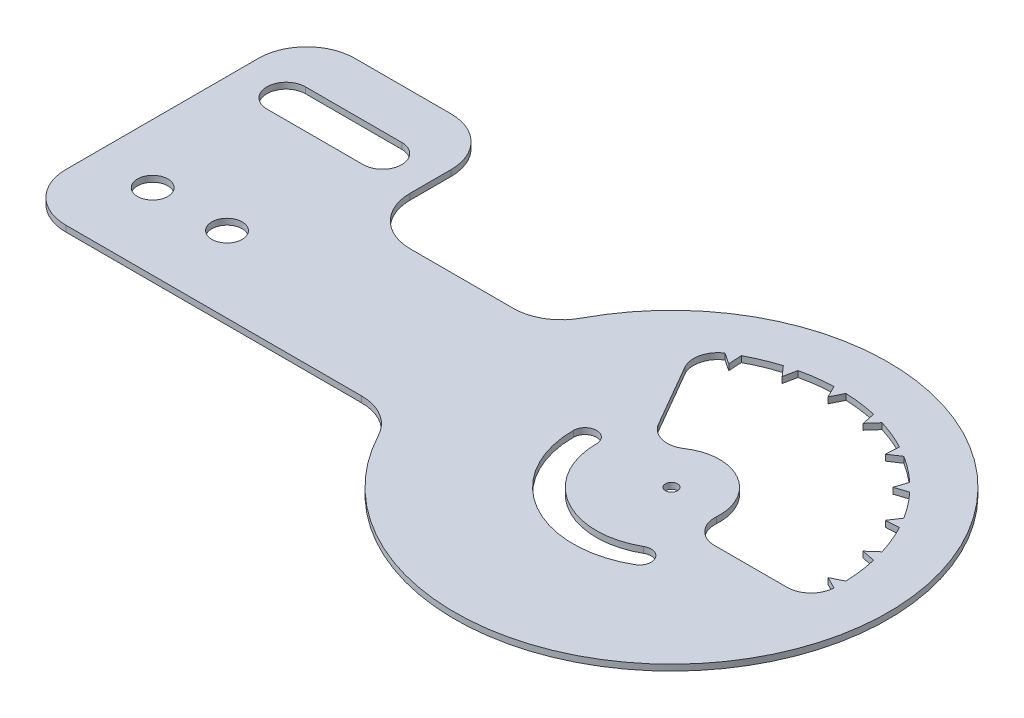
SolidWorks part; units mm, degrees
ref_plane "Front Plane" through (0, 0, 0) normal (0, 0, 1) x (1, 0, 0)
ref_plane "Top Plane" through (0, 0, 0) normal (0, 1, 0) x (1, 0, 0)
ref_plane "Right Plane" through (0, 0, 0) normal (1, 0, 0) x (0, 0, -1)
sketch "Sketch1" plane through (0, 0, 0) normal (0, 1, 0) x (1, 0, 0)
  line L0 (-61.723, 20) -> (-61.723, -20) construction
  line L1 (0, 0) -> (-61.723, 0) construction
  line L2 (-152.4, 43.5) -> (-152.4, -7.3)
  line L3 (-139.7, -20) -> (-61.723, -20)
  line L4 (-139.7, 38.1) -> (-114.3, 38.1) construction
  line L5 (-114.3, 38.1) -> (-101.6, 38.1) construction
  line L6 (-139.7, 38.1) -> (-152.4, 38.1) construction
  line L7 (-139.7, 56.2) -> (-114.3, 56.2)
  line L8 (-101.6, 32.7) -> (-101.6, 43.5)
  line L9 (-139.7, 33.02) -> (-114.3, 33.02)
  line L10 (-139.7, 43.18) -> (-114.3, 43.18)
  line L11 (-152.4, 5.63) -> (-152.4, 16.83) construction
  line L12 (-88.9, 20) -> (-61.723, 20)
  arc A0 (-50.5007, -26.7545) -> (-50.5007, 26.7545) centre (0, 0) ccw
  arc A1 (-61.723, -20) -> (-50.5007, -26.7545) centre (-61.723, -32.7) cw
  arc A2 (-61.723, 20) -> (-50.5007, 26.7545) centre (-61.723, 32.7) ccw
  arc A3 (-88.9, 20) -> (-101.6, 32.7) centre (-88.9, 32.7) cw
  arc A4 (-114.3, 56.2) -> (-101.6, 43.5) centre (-114.3, 43.5) cw
  arc A5 (-152.4, -7.3) -> (-139.7, -20) centre (-139.7, -7.3) ccw
  arc A6 (-152.4, 43.5) -> (-139.7, 56.2) centre (-139.7, 43.5) cw
  arc A7 (-139.7, 33.02) -> (-139.7, 43.18) centre (-139.7, 38.1) cw
  arc A8 (-114.3, 33.02) -> (-114.3, 43.18) centre (-114.3, 38.1) ccw
  circle A9 centre (-136.8, 0) radius 1.27
  circle A10 centre (-117.2, 0) radius 1.27
  circle A11 centre (0, 0) radius 1.5875
  dimension "D1" = 12.7
  dimension "D4" = 57.15
  dimension "D5" = 50.8
  dimension "D10" = 5.08
  dimension "D11" = 12.7
  dimension "D12" = 12.7
  dimension "D13" = 12.7
  dimension "D14" = 12.7
  dimension "D16" = 2.54
  dimension "D19" = 3.175
  dimension "D6" = 19.6
  dimension "D2" = 40
  dimension "D3" = 76.2
  dimension "D7" = 25.4
  dimension "D8" = 5.08
  dimension "D15" = 58.1
  dimension "D9" = 5.08
extrude "Boss-Extrude1" add sketch "Sketch1" along normal blind 1.5875 contours L7 A4 L8 A3 L12 A2 A0 A1 L3 A5 L2 A6
sketch "Sketch2" [suppressed] plane through (0, 0, 0) normal (0, -1, 0) x (1, 0, 0)
  line L0 (0, 0) -> (-17.9605, -17.9605) construction
  line L1 (0, 0) -> (24.5345, -6.574) construction
  line L2 (0, 0) -> (31.4309, 31.4309) construction
  line L3 (0, 0) -> (-42.9354, 11.5045) construction
  line L4 (-38.4705, 3.6327) -> (-20.0695, -1.2979)
  line L5 (31.4194, 22.4621) -> (17.949, 8.9917)
  line L6 (0, 0) -> (0, 44.45) construction
  line L7 (0, 41.275) -> (1.9574, 44.4069)
  line L8 (1.9574, 44.4069) -> (6.35, 51.435) construction
  line L9 (6.35, 51.435) -> (-6.35, 51.435) construction
  line L10 (-6.35, 51.435) -> (-1.9574, 44.4069) construction
  line L11 (-1.9574, 44.4069) -> (0, 41.275)
  line L12 (13.3841, 42.3871) -> (19.446, 48.0389) construction
  line L13 (10.6828, 39.8686) -> (13.3841, 42.3871)
  line L14 (9.6026, 43.4004) -> (10.6828, 39.8686)
  line L15 (7.1787, 51.3259) -> (9.6026, 43.4004) construction
  line L16 (19.446, 48.0389) -> (7.1787, 51.3259) construction
  line L17 (0, 0) -> (11.5045, 42.9354) construction
  line L18 (23.8986, 37.4788) -> (31.2168, 41.369) construction
  line L19 (20.6375, 35.7452) -> (23.8986, 37.4788)
  line L20 (20.5083, 39.4362) -> (20.6375, 35.7452)
  line L21 (20.2182, 47.719) -> (20.5083, 39.4362) construction
  line L22 (31.2168, 41.369) -> (20.2182, 47.719) construction
  line L23 (0, 0) -> (22.225, 38.4948) construction
  line L24 (32.7845, 30.0163) -> (40.8602, 31.8799) construction
  line L25 (29.1858, 29.1858) -> (32.7845, 30.0163)
  line L26 (30.0163, 32.7845) -> (29.1858, 29.1858)
  line L27 (31.8799, 40.8602) -> (30.0163, 32.7845) construction
  line L28 (40.8602, 31.8799) -> (31.8799, 40.8602) construction
  line L29 (0, 0) -> (31.4309, 31.4309) construction
  line L30 (-19.446, 48.0389) -> (-13.3841, 42.3871) construction
  line L31 (-13.3841, 42.3871) -> (-10.6828, 39.8686)
  line L32 (-10.6828, 39.8686) -> (-9.6026, 43.4004)
  line L33 (-9.6026, 43.4004) -> (-7.1787, 51.3259) construction
  line L34 (-7.1787, 51.3259) -> (-19.446, 48.0389) construction
  line L35 (0, 0) -> (-11.5045, 42.9354) construction
  line L36 (-31.2168, 41.369) -> (-23.8986, 37.4788) construction
  line L37 (-23.8986, 37.4788) -> (-20.6375, 35.7452)
  line L38 (-20.6375, 35.7452) -> (-20.5083, 39.4362)
  line L39 (-20.5083, 39.4362) -> (-20.2182, 47.719) construction
  line L40 (-20.2182, 47.719) -> (-31.2168, 41.369) construction
  line L41 (0, 0) -> (-22.225, 38.4948) construction
  line L42 (-40.8602, 31.8799) -> (-32.7845, 30.0163) construction
  line L43 (-32.7845, 30.0163) -> (-29.1858, 29.1858)
  line L44 (-29.1858, 29.1858) -> (-30.0163, 32.7845)
  line L45 (-30.0163, 32.7845) -> (-31.8799, 40.8602) construction
  line L46 (-31.8799, 40.8602) -> (-40.8602, 31.8799) construction
  line L47 (0, 0) -> (-31.4309, 31.4309) construction
  line L48 (-47.719, 20.2182) -> (-39.4362, 20.5083) construction
  line L49 (-39.4362, 20.5083) -> (-35.7452, 20.6375)
  line L50 (-35.7452, 20.6375) -> (-37.4788, 23.8986)
  line L51 (-37.4788, 23.8986) -> (-41.369, 31.2168) construction
  line L52 (-41.369, 31.2168) -> (-47.719, 20.2182) construction
  line L53 (0, 0) -> (-38.4948, 22.225) construction
  line L54 (-51.3259, 7.1787) -> (-43.4004, 9.6026) construction
  line L55 (-43.1763, 9.6711) -> (-39.8686, 10.6828)
  line L56 (-39.8686, 10.6828) -> (-42.3871, 13.3841)
  line L57 (-42.3871, 13.3841) -> (-48.0389, 19.446) construction
  line L58 (-48.0389, 19.446) -> (-51.3259, 7.1787) construction
  line L59 (0, 0) -> (-42.9354, 11.5045) construction
  arc A0 (30.0163, 32.7845) -> (23.8986, 37.4788) centre (0, 0) ccw
  arc A1 (8.9726, 8.9879) -> (-12.284, 3.2238) centre (0, 0) ccw
  arc A2 (31.4175, 31.4443) -> (31.4309, 31.4309) centre (26.9293, 26.9522) cw
  arc A3 (17.949, 8.9917) -> (8.9726, 8.9879) centre (13.4589, 13.4818) cw
  arc A4 (-20.0695, -1.2979) -> (-12.284, 3.2238) centre (-18.426, 4.8358) ccw
  arc A5 (-43.1763, 9.6711) -> (-38.4705, 3.6327) centre (-36.827, 9.7663) ccw
  arc A6 (38.4854, 22.2414) -> (32.7845, 30.0163) centre (0, 0) ccw
  arc A7 (42.9305, 11.5228) -> (32.7845, 30.0163) centre (0, 0) ccw
  arc A8 (44.45, 0.0189) -> (32.7845, 30.0163) centre (0, 0) ccw
  arc A9 (-39.4362, 20.5083) -> (-42.3871, 13.3841) centre (0, 0) ccw
  arc A10 (-32.7845, 30.0163) -> (-37.4788, 23.8986) centre (0, 0) ccw
  arc A11 (-32.7845, 30.0163) -> (-37.4788, 23.8986) centre (0, 0) ccw
  arc A12 (-23.8986, 37.4788) -> (-30.0163, 32.7845) centre (0, 0) ccw
  arc A13 (-23.8986, 37.4788) -> (-30.0163, 32.7845) centre (0, 0) ccw
  arc A14 (-23.8986, 37.4788) -> (-30.0163, 32.7845) centre (0, 0) ccw
  arc A15 (-13.3841, 42.3871) -> (-20.5083, 39.4362) centre (0, 0) ccw
  arc A16 (-13.3841, 42.3871) -> (-20.5083, 39.4362) centre (0, 0) ccw
  arc A17 (-13.3841, 42.3871) -> (-20.5083, 39.4362) centre (0, 0) ccw
  arc A18 (-13.3841, 42.3871) -> (-20.5083, 39.4362) centre (0, 0) ccw
  arc A19 (-1.9574, 44.4069) -> (-9.6026, 43.4004) centre (0, 0) ccw
  arc A20 (-1.9574, 44.4069) -> (-9.6026, 43.4004) centre (0, 0) ccw
  arc A21 (-1.9574, 44.4069) -> (-9.6026, 43.4004) centre (0, 0) ccw
  arc A22 (-1.9574, 44.4069) -> (-9.6026, 43.4004) centre (0, 0) ccw
  arc A23 (9.6026, 43.4004) -> (1.9574, 44.4069) centre (0, 0) ccw
  arc A24 (9.6026, 43.4004) -> (1.9574, 44.4069) centre (0, 0) ccw
  arc A25 (9.6026, 43.4004) -> (1.9574, 44.4069) centre (0, 0) ccw
  arc A26 (9.6026, 43.4004) -> (1.9574, 44.4069) centre (0, 0) ccw
  arc A27 (20.5083, 39.4362) -> (13.3841, 42.3871) centre (0, 0) ccw
  arc A28 (20.5083, 39.4362) -> (13.3841, 42.3871) centre (0, 0) ccw
  arc A29 (20.5083, 39.4362) -> (13.3841, 42.3871) centre (0, 0) ccw
  arc A30 (20.5083, 39.4362) -> (13.3841, 42.3871) centre (0, 0) ccw
  arc A31 (30.0163, 32.7845) -> (23.8986, 37.4788) centre (0, 0) ccw
  arc A32 (30.0163, 32.7845) -> (23.8986, 37.4788) centre (0, 0) ccw
  arc A33 (30.0163, 32.7845) -> (23.8986, 37.4788) centre (0, 0) ccw
  arc A34 (32.5239, 29.9561) -> (31.4194, 22.4621) centre (26.9293, 26.9522) cw
  arc A35 (31.4309, 31.4309) -> (31.4175, 31.4443) centre (0, 0) ccw
  arc A36 (31.4309, 31.4309) -> (31.4175, 31.4443) centre (0, 0) ccw
  arc A37 (31.4309, 31.4309) -> (31.4175, 31.4443) centre (0, 0) ccw
  point P13 (35.5888, 26.6315)
  point P20 (-44.1501, 5.1545)
  point P54 (0, 0)
  point P85 (0, 0)
  dimension "D3" = 6.35
  dimension "D5" = 12.7
  dimension "D6" = 6.35
  dimension "D1" = 120
  dimension "D2" = 44.45
  dimension "D4" = 6.35
  dimension "D7" = 3.175
  dimension "D8" = 12.7
  dimension "D9" = 10.16
  dimension "D11" = 15
  dimension "D12" = 6
  dimension "D13" = 15
  dimension "D14" = 44.45
  dimension "D10" = 4
extrude "Cut-Extrude1" [suppressed] cut sketch "Sketch2" against normal through all contours A34 L25 L26 A0 L19 L20 A27 L13 L14 A23 L7 L11 A19 L32 L31 A15 L38 L37 A12 L44 L43 A10 L50 L49 A9 L56 L55 A5 L4 A4 A1 A3 L5
sketch "Sketch3" [suppressed] plane through (0, 0, 0) normal (0, -1, 0) x (1, 0, 0)
  line L0 (0, 0) -> (-17.9605, -17.9605) construction
  line L1 (0, 0) -> (24.5345, -6.574) construction
  arc A0 (-17.9605, -17.9605) -> (24.5345, -6.574) centre (0, 0) ccw construction
  arc A1 (-20.1158, -20.1158) -> (27.4787, -7.3629) centre (0, 0) ccw
  arc A2 (-15.8053, -15.8053) -> (21.5904, -5.7851) centre (0, 0) ccw
  arc A3 (-20.1158, -20.1158) -> (-15.8053, -15.8053) centre (-17.9605, -17.9605) cw
  arc A4 (27.4787, -7.3629) -> (21.5904, -5.7851) centre (24.5345, -6.574) ccw
  dimension "D2" = 3.048
  dimension "D1" = 120
  dimension "D3" = 3.048
extrude "Cut-Extrude2" [suppressed] cut sketch "Sketch3" against normal through all
sketch "Sketch5" plane through (0, 0, 0) normal (0, -1, 0) x (1, 0, 0)
  line L0 (0, 0) -> (-22.8599, -0.055) construction
  line L1 (0, 0) -> (11.3823, 19.8248) construction
  arc A0 (-22.8599, -0.055) -> (11.3823, 19.8248) centre (0, 0) cw construction
  arc A1 (-19.8119, -0.0477) -> (9.8647, 17.1815) centre (0, 0) cw
  arc A2 (-25.9079, -0.0623) -> (12.9, 22.4681) centre (0, 0) cw
  arc A3 (-19.8119, -0.0477) -> (-25.9079, -0.0623) centre (-22.8599, -0.055) cw
  arc A4 (9.8647, 17.1815) -> (12.9, 22.4681) centre (11.3823, 19.8248) ccw
  dimension "D2" = 3.048
  dimension "D1" = 120
  dimension "D3" = 3.048
extrude "Cut-Extrude3" cut sketch "Sketch5" against normal through all
sketch "Sketch6" plane through (0, 0, 0) normal (0, -1, 0) x (1, 0, 0)
  line L0 (-22.8599, -0.055) -> (0, 0) construction
  line L1 (0, 0) -> (-22.225, -38.4948) construction
  line L2 (-25.6385, -29.1672) -> (-16.1029, -12.6511)
  line L3 (38.0788, 7.62) -> (19.0076, 7.62)
  line L4 (0, 0) -> (44.45, 0) construction
  line L5 (41.275, 0) -> (44.4221, -1.5736)
  line L6 (44.4221, -1.5736) -> (53.975, -6.35) construction
  line L7 (53.975, -6.35) -> (53.975, 6.35) construction
  line L8 (53.975, 6.35) -> (44.4221, 1.5736) construction
  line L9 (44.4221, 1.5736) -> (41.275, 0)
  line L10 (0, 0) -> (42.9354, -11.5045) construction
  line L11 (39.8686, -10.6828) -> (42.5012, -13.0172)
  line L12 (42.5012, -13.0172) -> (50.4923, -20.1034) construction
  line L13 (50.4923, -20.1034) -> (53.7793, -7.8361) construction
  line L14 (53.7793, -7.8361) -> (43.3158, -9.9773) construction
  line L15 (43.3158, -9.9773) -> (39.8686, -10.6828)
  line L16 (0, 0) -> (38.4948, -22.225) construction
  line L17 (35.7452, -20.6375) -> (37.6839, -23.5738)
  line L18 (37.6839, -23.5738) -> (43.5687, -32.4868) construction
  line L19 (43.5687, -32.4868) -> (49.9187, -21.4882) construction
  line L20 (49.9187, -21.4882) -> (39.2575, -20.8483) construction
  line L21 (39.2575, -20.8483) -> (35.7452, -20.6375)
  line L22 (0, 0) -> (31.4309, -31.4309) construction
  line L23 (29.1858, -29.1858) -> (30.2985, -32.5239)
  line L24 (30.2985, -32.5239) -> (33.676, -42.6562) construction
  line L25 (33.676, -42.6562) -> (42.6562, -33.676) construction
  line L26 (42.6562, -33.676) -> (32.5239, -30.2985) construction
  line L27 (32.5239, -30.2985) -> (29.1858, -29.1858)
  line L28 (0, 0) -> (22.225, -38.4948) construction
  line L29 (20.6375, -35.7452) -> (20.8483, -39.2575)
  line L30 (20.8483, -39.2575) -> (21.4882, -49.9187) construction
  line L31 (21.4882, -49.9187) -> (32.4868, -43.5687) construction
  line L32 (32.4868, -43.5687) -> (23.5738, -37.6839) construction
  line L33 (23.5738, -37.6839) -> (20.6375, -35.7452)
  line L34 (0, 0) -> (11.5045, -42.9354) construction
  line L35 (10.6828, -39.8686) -> (9.9773, -43.3158)
  line L36 (9.9773, -43.3158) -> (7.8361, -53.7793) construction
  line L37 (7.8361, -53.7793) -> (20.1034, -50.4923) construction
  line L38 (20.1034, -50.4923) -> (13.0172, -42.5012) construction
  line L39 (13.0172, -42.5012) -> (10.6828, -39.8686)
  line L40 (0, 0) -> (0, -44.45) construction
  line L41 (0, -41.275) -> (-1.5736, -44.4221)
  line L42 (-1.5736, -44.4221) -> (-6.35, -53.975) construction
  line L43 (-6.35, -53.975) -> (6.35, -53.975) construction
  line L44 (6.35, -53.975) -> (1.5736, -44.4221) construction
  line L45 (1.5736, -44.4221) -> (0, -41.275)
  line L46 (0, 0) -> (-11.5045, -42.9354) construction
  line L47 (-10.6828, -39.8686) -> (-9.9773, -43.3158)
  line L48 (-9.9773, -43.3158) -> (-7.8361, -53.7793) construction
  line L49 (-7.8361, -53.7793) -> (-20.1034, -50.4923) construction
  line L50 (-20.1034, -50.4923) -> (-13.0172, -42.5012) construction
  line L51 (-13.0172, -42.5012) -> (-10.6828, -39.8686)
  line L52 (-20.6375, -35.7452) -> (-20.8483, -39.2575)
  line L53 (-20.8483, -39.2575) -> (-21.4882, -49.9187) construction
  line L54 (-21.4882, -49.9187) -> (-32.4868, -43.5687) construction
  line L55 (-32.4868, -43.5687) -> (-23.5738, -37.6839) construction
  line L56 (-23.5738, -37.6839) -> (-20.6375, -35.7452)
  arc A0 (-23.4958, -37.7326) -> (44.4253, 1.4817) centre (0, 0) ccw
  arc A1 (-7.0691, -10.5507) -> (12.6717, 0.8467) centre (0, 0) ccw
  arc A2 (-23.4958, -37.7326) -> (-25.6385, -29.1672) centre (-20.1393, -32.3422) cw
  arc A3 (44.4253, 1.4817) -> (38.0788, 7.62) centre (38.0788, 1.27) ccw
  arc A4 (12.6717, 0.8467) -> (19.0076, 7.62) centre (19.0076, 1.27) cw
  arc A5 (-16.1029, -12.6511) -> (-7.0691, -10.5507) centre (-10.6037, -15.8261) cw
  arc A6 (-20.6375, -35.7452) -> (41.275, 0) centre (0, 0) ccw construction
  point P59 (0, 0)
  point P77 (0, 0)
  dimension "D4" = 6.35
  dimension "D6" = 12.7
  dimension "D15" = 15
  dimension "D8" = 12.7
  dimension "D9" = 12.7
  dimension "D5" = 3.175
  dimension "D1" = 15
  dimension "D2" = 120
  dimension "D3" = 44.45
  dimension "D7" = 7.62
  dimension "D11" = 15
  dimension "D13" = 15
  dimension "D14" = 15
  dimension "D16" = 15
  dimension "D10" = 15
  dimension "D12" = 15
extrude "Cut-Extrude4" cut sketch "Sketch6" against normal through all
hole_wizard "Ø8.0mm Dowel Hole1" positions "Sketch8" profile "Sketch7" hole size "Ø8.0" standard "ANSI Metric"
sketch "Sketch8" plane through (0, 1.5875, 0) normal (0, 1, 0) x (1, 0, 0)
  point P0 (-136.8, 0)
  point P3 (-117.2, 0)
sketch "Sketch7" plane through (-136.8, 1.5875, 0) normal (1, 0, 0) x (0, 0, 1)
  line L0 (0, 0) -> (0, 7.4834)
  line L1 (0, 7.4834) -> (4, 5.08)
  line L2 (4, 5.08) -> (4, 0)
  line L5 (4, 0) -> (0, 0)
  line L10 (0, 7.4834) -> (-4, 5.08) construction
  line L11 (0, -6.35) -> (0, 107.95) construction
  dimension "Hole Dia." = 8
  dimension "Hole Depth" = 5.08
  dimension "Drill Angle" = 118
